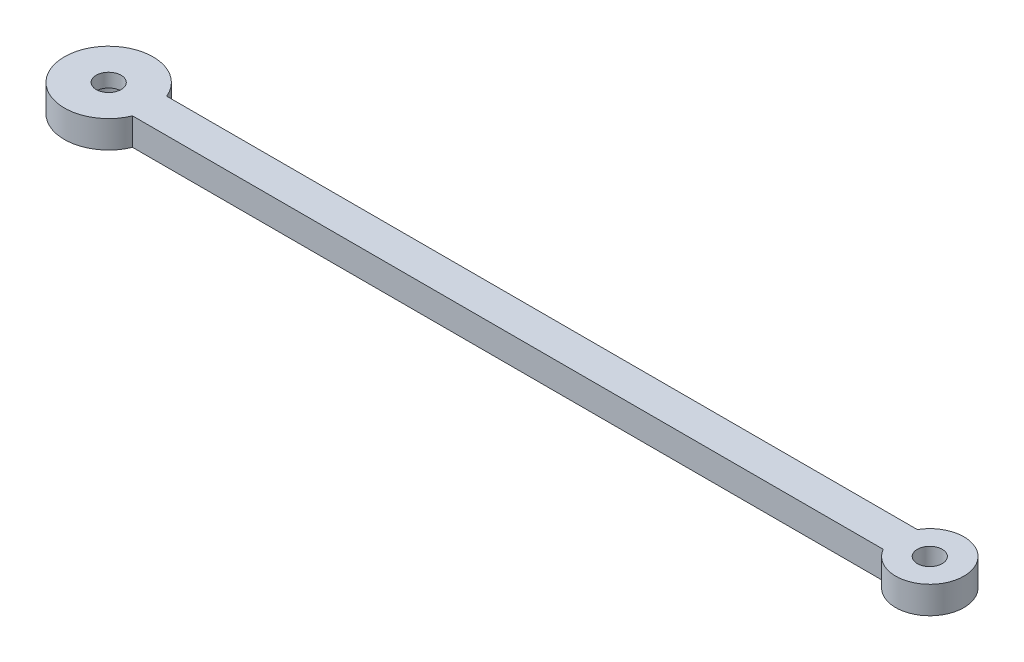
SolidWorks part; units mm, degrees
ref_plane "Front Plane" through (0, 0, 0) normal (0, 0, 1) x (1, 0, 0)
ref_plane "Top Plane" through (0, 0, 0) normal (0, 1, 0) x (1, 0, 0)
ref_plane "Right Plane" through (0, 0, 0) normal (1, 0, 0) x (0, 0, -1)
sketch "Sketch1" plane through (0, 0, 0) normal (0, 1, 0) x (1, 0, 0)
  line L0 (-55, 2.5) -> (55, 2.5)
  line L1 (-55, -2.5) -> (55, -2.5)
  line L2 (-55, 0) -> (55, 0) construction
  arc A1 (-55, 2.5) -> (-55, -2.5) centre (-61, 0) ccw
  arc A2 (55, 2.5) -> (55, -2.5) centre (59.3301, 0) cw
  dimension "D2" = 55
  dimension "D3" = 6.5
  dimension "D7" = 5
  dimension "D1" = 5
  dimension "D4" = 110
  dimension "D5" = 110
  dimension "D6" = 2.5
extrude "Boss-Extrude1" add sketch "Sketch1" along normal blind 4
sketch "Sketch3" plane through (0, 0, 0) normal (0, -1, 0) x (1, 0, 0)
  circle A0 centre (-61, 0) radius 3.5
  dimension "D1" = 7
extrude "Cut-Extrude2" cut sketch "Sketch3" against normal blind 2
sketch "Sketch2" plane through (0, 4, 0) normal (0, 1, 0) x (1, 0, 0)
  circle A0 centre (-61, 0) radius 1.825
  circle A1 centre (59.3301, 0) radius 1.825
  dimension "D1" = 3.65
  dimension "D2" = 3.65
extrude "Cut-Extrude1" cut sketch "Sketch2" against normal through all
